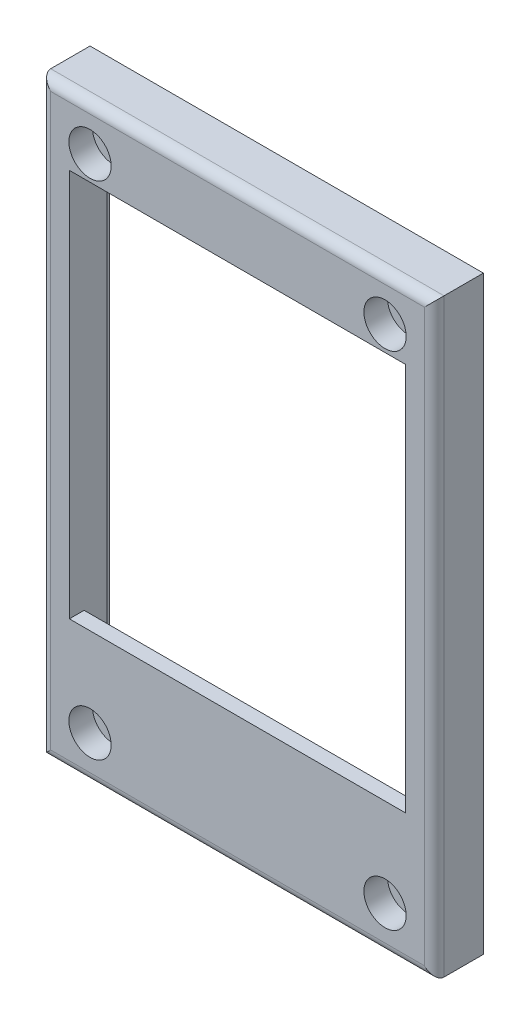
SolidWorks part; units mm, degrees
ref_plane "Front Plane" through (0, 0, 0) normal (1, 0, 0) x (0, 1, 0)
ref_plane "Top Plane" through (0, 0, 0) normal (0, 0, 1) x (0, 1, 0)
ref_plane "Right Plane" through (0, 0, 0) normal (0, 1, 0) x (-1, 0, 0)
sketch "Sketch1" plane through (0, 0, 0) normal (0, 0, 1) x (0, 1, 0)
  line L0 (0, -20) -> (60, -20) construction
  line L1 (0, 0) -> (60, 0)
  line L2 (0, 0) -> (0, -40)
  line L3 (0, -40) -> (60, -40)
  line L4 (60, 0) -> (60, -40)
  line L5 (30, 0) -> (30, -40) construction
  dimension "D1" = 60
  dimension "D2" = 40
extrude "Boss-Extrude1" add sketch "Sketch1" along normal blind 5
sketch "Sketch2" plane through (0, 0, 0) normal (0, 0, -1) x (1, 0, 0)
  line L0 (0, -30) -> (40, -30) construction
  line L1 (0, -60) -> (0, 0) construction
  line L2 (40, 0) -> (40, -60) construction
  line L4 (2.9, -7) -> (37.1, -7)
  line L5 (2.9, -7) -> (2.9, -53)
  line L6 (2.9, -53) -> (37.1, -53)
  line L7 (37.1, -7) -> (37.1, -53)
  line L8 (2.9, -7) -> (37.1, -53) construction
  line L9 (2.9, -53) -> (37.1, -7) construction
  point P6 (20, -30)
  dimension "D1" = 34.2
  dimension "D2" = 46
extrude "Cut-Extrude1" cut sketch "Sketch2" against normal through all
sketch "Sketch3" plane through (0, 0, 5) normal (0, 0, 1) x (1, 0, 0)
  line L0 (0, 55.5) -> (40, 55.5) construction
  line L1 (0, 60) -> (0, 0) construction
  line L2 (40, 0) -> (40, 60) construction
  line L3 (0, 4.5) -> (40, 4.5) construction
  line L4 (0, 30) -> (40, 30) construction
  line L5 (20, 60) -> (20, 0) construction
  line L6 (40, 60) -> (0, 60) construction
  line L7 (0, 0) -> (40, 0) construction
  circle A0 centre (5, 4.5) radius 1.15
  circle A1 centre (35, 4.5) radius 1.15
  circle A2 centre (5, 55.5) radius 1.15
  circle A3 centre (35, 55.5) radius 1.15
  dimension "D5" = 2.3
  dimension "D6" = 2.3
  dimension "D7" = 2.3
  dimension "D8" = 2.3
  dimension "D1" = 25.5
  dimension "D2" = 25.5
  dimension "D3" = 15
  dimension "D4" = 15
  dimension "D9" = 15
  dimension "D10" = 15
extrude "Cut-Extrude2" cut sketch "Sketch3" against normal through all
sketch "Sketch4" plane through (0, 0, 5) normal (0, 0, 1) x (1, 0, 0)
  circle A0 centre (5, 55.5) radius 2.15
  circle A1 centre (35, 55.5) radius 2.15
  circle A2 centre (5, 4.5) radius 2.15
  circle A3 centre (35, 4.5) radius 2.15
  dimension "D1" = 4.3
  dimension "D2" = 4.3
  dimension "D3" = 4.3
  dimension "D4" = 4.3
extrude "Cut-Extrude3" cut sketch "Sketch4" against normal blind 2.4
sketch "Sketch5" plane through (0, 0, 0) normal (0, 0, -1) x (1, 0, 0)
  line L0 (0, -30) -> (40, -30) construction
  line L1 (0, -60) -> (0, 0) construction
  line L2 (40, 0) -> (40, -60) construction
  line L3 (20, 0) -> (20, -60) construction
  line L4 (0, 0) -> (40, 0) construction
  line L5 (40, -60) -> (0, -60) construction
  line L7 (38, -1.75) -> (2, -1.75)
  line L8 (38, -1.75) -> (38, -58.25)
  line L9 (38, -58.25) -> (2, -58.25)
  line L10 (2, -1.75) -> (2, -58.25)
  line L11 (38, -1.75) -> (2, -58.25) construction
  line L12 (38, -58.25) -> (2, -1.75) construction
  point P12 (20, -30)
  dimension "D1" = 36
  dimension "D2" = 56.5
extrude "Cut-Extrude4" cut sketch "Sketch5" against normal blind 1.2
sketch "Sketch6" plane through (0, 0, 1.2) normal (0, 0, -1) x (1, 0, 0)
  line L0 (20, -53) -> (20, -58.25) construction
  line L1 (2.9, -53) -> (37.1, -53) construction
  line L2 (2, -58.25) -> (38, -58.25) construction
  line L4 (32.5, -54.125) -> (7.5, -54.125)
  line L5 (32.5, -54.125) -> (32.5, -57.125)
  line L6 (32.5, -57.125) -> (7.5, -57.125)
  line L7 (7.5, -54.125) -> (7.5, -57.125)
  line L8 (32.5, -54.125) -> (7.5, -57.125) construction
  line L9 (32.5, -57.125) -> (7.5, -54.125) construction
  point P6 (20, -55.625)
  dimension "D1" = 25
  dimension "D2" = 3
extrude "Cut-Extrude5" cut sketch "Sketch6" against normal blind 2.5
fillet "Fillet1" radius 1 4 edges at (20, 0, 5) (40, 30, 5) (20, 60, 5) (0, 30, 5)
sketch "Sketch7" plane through (2.9, 0, 0) normal (1, 0, 0) x (0, 1, 0)
  line L1 (7, 5) -> (13.5, 5)
  line L2 (7, 5) -> (7, 3.5)
  line L3 (7, 3.5) -> (13.5, 3.5)
  line L4 (13.5, 5) -> (13.5, 3.5)
  dimension "D1" = 6.5
  dimension "D2" = 1.5
extrude "Boss-Extrude2" add sketch "Sketch7" along normal up to next
